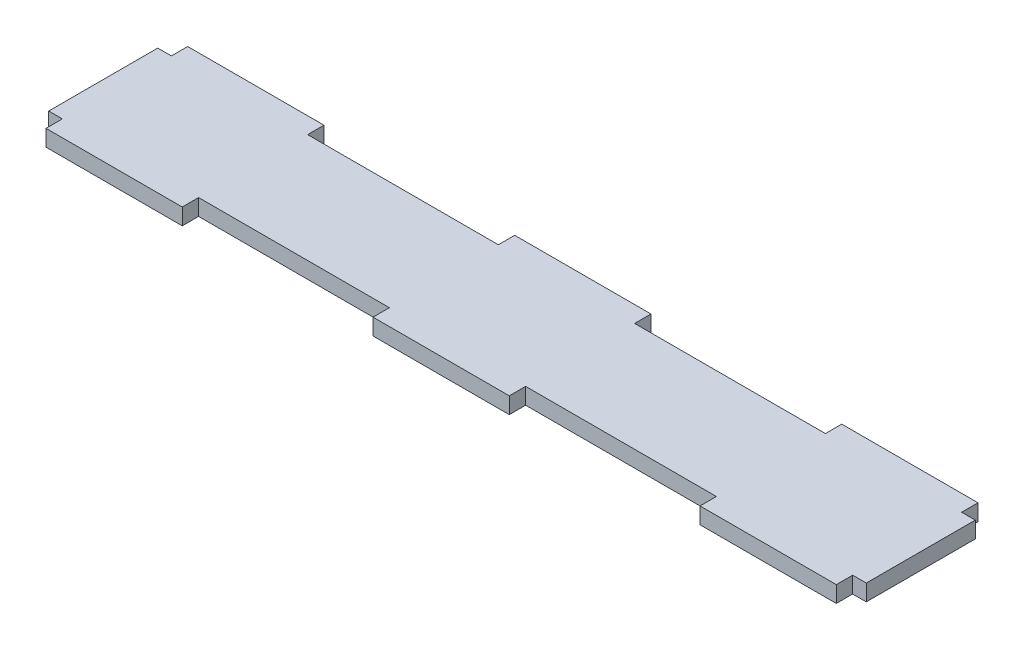
SolidWorks part; units mm, degrees
ref_plane "前视基准面" through (0, 0, 0) normal (0, 0, 1) x (1, 0, 0)
ref_plane "上视基准面" through (0, 0, 0) normal (0, 1, 0) x (1, 0, 0)
ref_plane "右视基准面" through (0, 0, 0) normal (1, 0, 0) x (0, 0, -1)
other "Configuration Table"
sketch "草图1" plane through (0, 0, 0) normal (0, 1, 0) x (1, 0, 0)
  line L0 (47.5, 10) -> (47.5, 13)
  line L1 (-75, 10) -> (75, 10)
  line L2 (-75, 10) -> (-75, -10)
  line L3 (-75, -10) -> (75, -10)
  line L4 (75, 10) -> (75, -10)
  line L5 (-75, 10) -> (75, -10) construction
  line L6 (-75, -10) -> (75, 10) construction
  line L7 (-12.5, 10) -> (12.5, 10)
  line L8 (-12.5, 10) -> (-12.5, 13)
  line L9 (-12.5, 13) -> (12.5, 13)
  line L10 (12.5, 10) -> (12.5, 13)
  line L11 (47.5, 10) -> (72.5, 10)
  line L12 (72.5, 10) -> (72.5, 13)
  line L13 (47.5, 13) -> (72.5, 13)
  line L14 (0, 18.5263) -> (0, -15.8947) construction
  line L15 (-47.5, 13) -> (-72.5, 13)
  line L16 (-72.5, 10) -> (-72.5, 13)
  line L17 (-47.5, 10) -> (-72.5, 10)
  line L18 (-47.5, 10) -> (-47.5, 13)
  line L19 (-75, 0) -> (-61.7895, 0) construction
  line L20 (-47.5, -10) -> (-47.5, -13)
  line L21 (-47.5, -10) -> (-72.5, -10)
  line L22 (-72.5, -10) -> (-72.5, -13)
  line L23 (-47.5, -13) -> (-72.5, -13)
  line L24 (47.5, -13) -> (72.5, -13)
  line L25 (72.5, -10) -> (72.5, -13)
  line L26 (47.5, -10) -> (72.5, -10)
  line L27 (12.5, -10) -> (12.5, -13)
  line L28 (-12.5, -13) -> (12.5, -13)
  line L29 (-12.5, -10) -> (-12.5, -13)
  line L30 (-12.5, -10) -> (12.5, -10)
  line L31 (-75, -10) -> (75, -10)
  line L32 (47.5, -10) -> (47.5, -13)
  point P0 (0, 0)
  point P10 (0, 13)
  dimension "D1" = 20
  dimension "D2" = 150
  dimension "D3" = 25
  dimension "D4" = 3
  dimension "D6" = 35
  dimension "D5" = 2
extrude "凸台-拉伸1" add sketch "草图1" along normal blind 3 contours L4 L1 L2 L3 | L1 L18 L15 L16 | L23 L20 L3 L22 | L3 L29 L28 L27 | L1 L10 L9 L8 | L13 L0 L1 L12 | L3 L32 L24 L25
